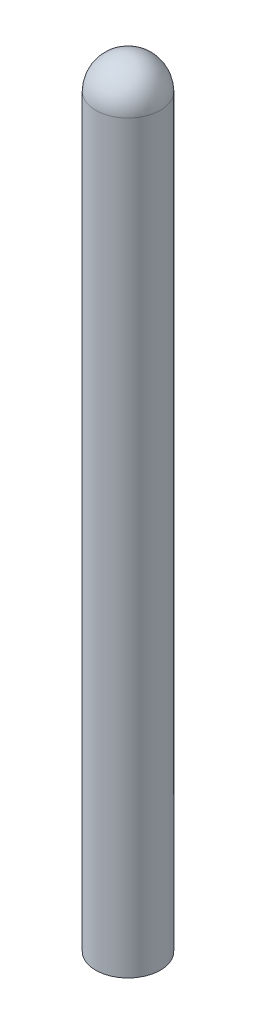
SolidWorks part; units mm, degrees
material "Plain Carbon Steel"
ref_plane "Front Plane" through (0, 0, 0) normal (0, 0, 1) x (1, 0, 0)
ref_plane "Top Plane" through (0, 0, 0) normal (0, 1, 0) x (1, 0, 0)
ref_plane "Right Plane" through (0, 0, 0) normal (1, 0, 0) x (0, 0, -1)
sketch "Sketch2" plane through (0, 0, 0) normal (0, 1, 0) x (1, 0, 0)
  circle A0 centre (0, 0) radius 3.175
  dimension "D1" = 6.35
extrude "Boss-Extrude1" add sketch "Sketch2" along normal blind 76.2
fillet "Fillet1" radius 3.175 1 edges at (0, 76.2, 3.175)
